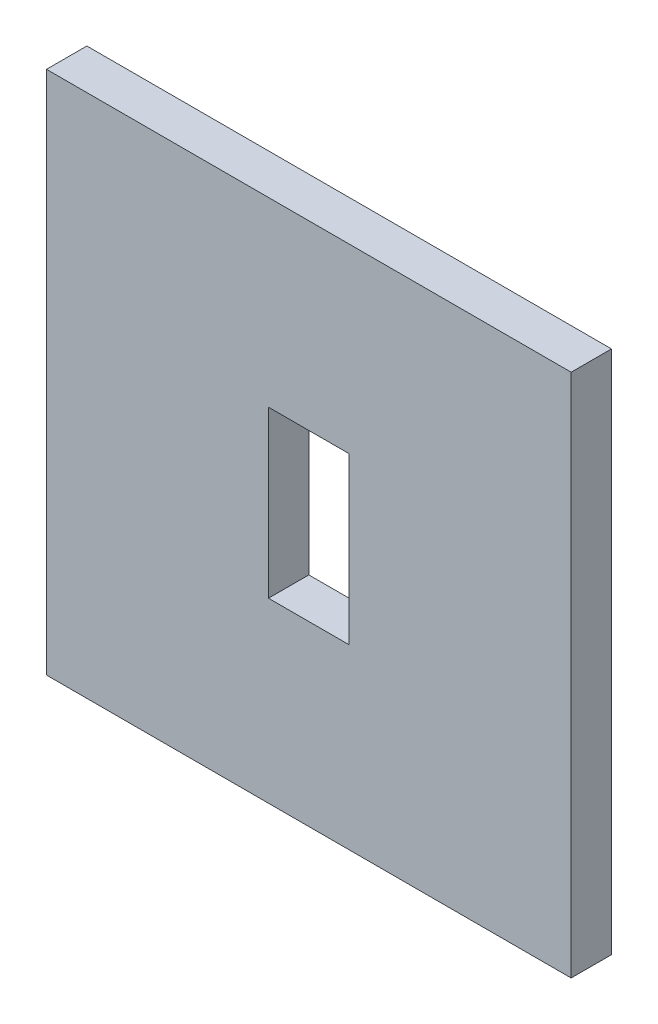
SolidWorks part; units mm, degrees
ref_plane "Plan de face" through (0, 0, 0) normal (0, 0, 1) x (1, 0, 0)
ref_plane "Plan de dessus" through (0, 0, 0) normal (0, 1, 0) x (1, 0, 0)
ref_plane "Plan de droite" through (0, 0, 0) normal (1, 0, 0) x (0, 0, -1)
sketch "Esquisse1" plane through (0, 0, 0) normal (0, 0, 1) x (1, 0, 0)
  line L1 (0, 0) -> (130, 0)
  line L2 (0, 0) -> (0, -130)
  line L3 (0, -130) -> (130, -130)
  line L4 (130, 0) -> (130, -130)
  dimension "D1" = 130
  dimension "D2" = 130
extrude "Boss.-Extru.1" add sketch "Esquisse1" along normal blind 10
sketch "Esquisse2" plane through (0, 0, 10) normal (0, 0, 1) x (1, 0, 0)
  line L0 (0, 0) -> (0, -130) construction
  line L1 (55, -45) -> (75, -45)
  line L2 (55, -45) -> (55, -86)
  line L3 (55, -86) -> (75, -86)
  line L4 (75, -45) -> (75, -86)
  line L5 (130, 0) -> (0, 0) construction
  dimension "D1" = 41
  dimension "D2" = 20
  dimension "D3" = 55
  dimension "D4" = 45
extrude "Enlèv. mat.-Extru.1" cut sketch "Esquisse2" against normal blind 10
